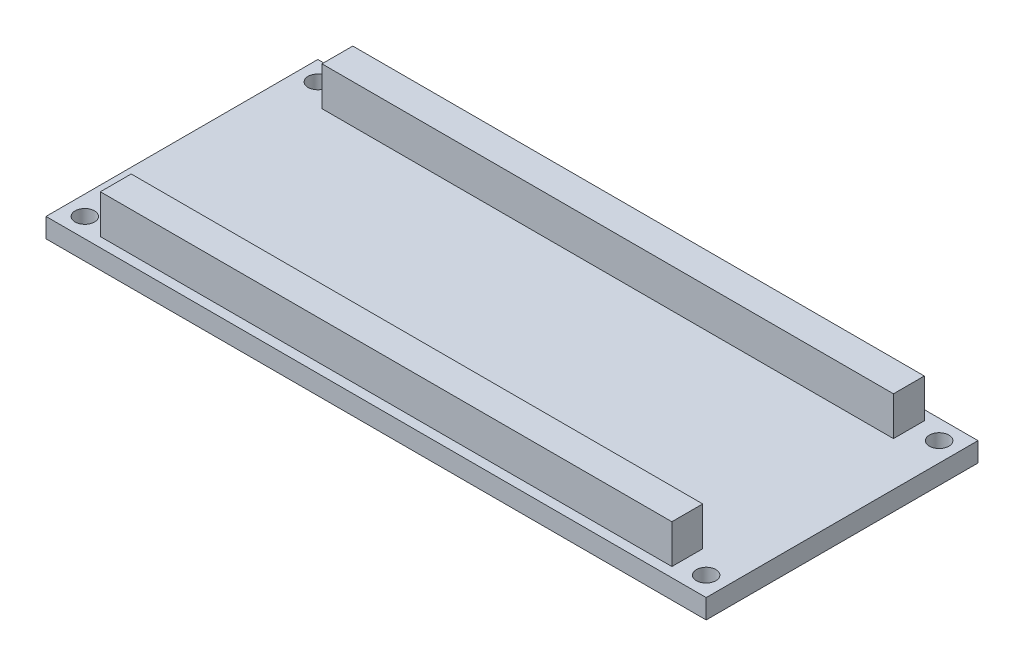
SolidWorks part; units mm, degrees
ref_plane "Front Plane" through (0, 0, 0) normal (0, 0, 1) x (1, 0, 0)
ref_plane "Top Plane" through (0, 0, 0) normal (0, 1, 0) x (1, 0, 0)
ref_plane "Right Plane" through (0, 0, 0) normal (1, 0, 0) x (0, 0, -1)
sketch "Sketch2" plane through (0, 0, 0) normal (0, 1, 0) x (1, 0, 0)
  line L1 (-21.59, -8.89) -> (21.59, -8.89)
  line L2 (-21.59, -8.89) -> (-21.59, 8.89)
  line L3 (-21.59, 8.89) -> (21.59, 8.89)
  line L4 (21.59, -8.89) -> (21.59, 8.89)
  line L5 (-21.59, -8.89) -> (21.59, 8.89) construction
  line L6 (-21.59, 8.89) -> (21.59, -8.89) construction
  point P0 (0, 0)
  dimension "D1" = 43.18
  dimension "D2" = 17.78
extrude "Boss-Extrude1" add sketch "Sketch2" along normal blind 1.27
sketch "Sketch3" plane through (0, 1.27, 0) normal (0, 1, 0) x (1, 0, 0)
  line L0 (21.59, 8.89) -> (-21.59, 8.89) construction
  line L1 (-21.59, 8.89) -> (-21.59, -8.89) construction
  circle A0 centre (-20.32, 7.62) radius 0.635
  dimension "D1" = 1.27
  dimension "D3" = 1.27
  dimension "D2" = 1.27
extrude "Cut-Extrude1" cut sketch "Sketch3" against normal through all both and the other way through all
mirror "Mirror1" about plane through (0, 0, 0) normal (1, 0, 0) of "Cut-Extrude1" second plane through (0, 0, 0) second plane normal (0, 0, 1)
sketch "Sketch4" plane through (0, 1.27, 0) normal (0, 1, 0) x (1, 0, 0)
  line L1 (-18.6686, -8.255) -> (18.7125, -8.255)
  line L2 (-18.6686, -8.255) -> (-18.6686, -6.2383)
  line L3 (-18.6686, -6.2383) -> (18.7125, -6.2383)
  line L4 (18.7125, -8.255) -> (18.7125, -6.2383)
extrude "Boss-Extrude2" add sketch "Sketch4" along normal blind 2.54
mirror "Mirror2" about plane through (0, 0, 0) normal (0, 0, 1) of "Boss-Extrude2"
